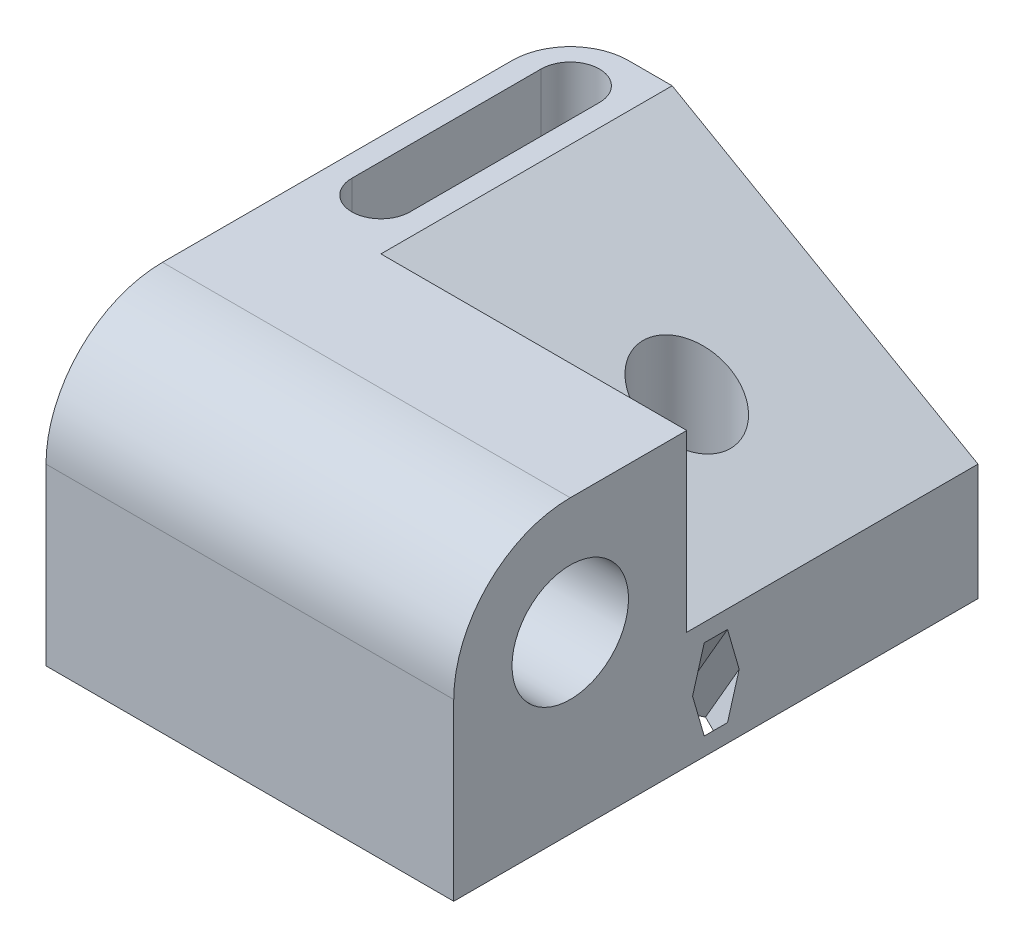
SolidWorks part; units mm, degrees
material "Cast Alloy Steel"
ref_plane "Front Plane" through (0, 0, 0) normal (0, 0, 1) x (1, 0, 0)
ref_plane "Top Plane" through (0, 0, 0) normal (0, 1, 0) x (1, 0, 0)
ref_plane "Right Plane" through (0, 0, 0) normal (1, 0, 0) x (0, 0, -1)
sketch "Sketch1" plane through (0, 0, 0) normal (0, 1, 0) x (1, 0, 0)
  line L0 (-52.5, -7.5) -> (-52.5, -72.5) construction
  line L1 (-50, -90) -> (70, -90)
  line L2 (-70, -70) -> (-70, 90)
  line L3 (-70, 90) -> (70, 90)
  line L4 (70, -90) -> (70, 90)
  line L5 (-70, -90) -> (70, 90) construction
  line L6 (-70, 90) -> (70, -90) construction
  line L7 (-42.5, -7.5) -> (-42.5, -72.5)
  line L8 (-62.5, -7.5) -> (-62.5, -72.5)
  arc A0 (-50, -90) -> (-70, -70) centre (-50, -70) cw
  arc A1 (-42.5, -7.5) -> (-62.5, -7.5) centre (-52.5, -7.5) ccw
  arc A2 (-62.5, -72.5) -> (-42.5, -72.5) centre (-52.5, -72.5) ccw
  circle A3 centre (25, -35) radius 15
  point P0 (0, 0)
  point P11 (-52.5, -40)
  dimension "D3" = 20
  dimension "D5" = 10
  dimension "D8" = 30
  dimension "D1" = 140
  dimension "D2" = 180
  dimension "D4" = 65
  dimension "D6" = 82.5
  dimension "D7" = 17.5
  dimension "D9" = 45
  dimension "D10" = 55
extrude "Boss-Extrude1" add sketch "Sketch1" along normal blind 100
sketch "Sketch2" plane through (0, 0, 90) normal (0, 0, 1) x (1, 0, 0)
  line L0 (-35, 100) -> (70, 40)
  line L1 (-50, 100) -> (70, 100) construction
  line L2 (70, 100) -> (70, 0) construction
  line L3 (70, 40) -> (70, 100)
  line L4 (70, 100) -> (-35, 100)
  dimension "D1" = 105
  dimension "D2" = 60
extrude "Cut-Extrude1" cut sketch "Sketch2" against normal blind 100
fillet "Fillet1" radius 40 1 edges at (0, 100, -90)
sketch "Sketch3" plane through (70, 0, 0) normal (1, 0, 0) x (0, 0, -1)
  line L0 (10, 40) -> (-90, 40) construction
  circle A0 centre (50, 60) radius 20
  point P2 (0, 0)
  point P3 (0, 0)
  point P4 (0, 0)
  point P5 (0, 0)
  dimension "D1" = 40
extrude "Cut-Extrude2" cut sketch "Sketch3" against normal blind 105
sketch "Sketch5" plane through (70, 0, 0) normal (1, 0, 0) x (0, 0, -1)
  line L0 (-90, 0) -> (90, 0) construction
  line L1 (90, 60) -> (90, 0) construction
  point P0 (0, 20)
  point P5 (0, 0)
  point P6 (0, 0)
  point P7 (0, 0)
  point P8 (0, 0)
  point P9 (0, 0)
  dimension "D1" = 20
  dimension "D2" = 90
ref_plane "Plane1" through (60.8013, 105.3109, 0) normal (0.5, 0.866, 0) x (0, 0, -1)
sketch "Sketch6" plane through (60.8013, 105.3109, 0) normal (0.5, 0.866, 0) x (0, 0, -1)
  line L1 (8, -50.6218) -> (4, -43.6936)
  line L2 (4, -43.6936) -> (-4, -43.6936)
  line L3 (-4, -43.6936) -> (-8, -50.6218)
  line L4 (-8, -50.6218) -> (-4, -57.55)
  line L5 (-4, -57.55) -> (4, -57.55)
  line L6 (4, -57.55) -> (8, -50.6218)
  circle A0 centre (0, -50.6218) radius 6.9282 construction
  point P1 (0, 0)
  point P9 (7.8751, -50.6218)
  point P10 (0, 0)
  point P11 (0, 0)
  point P12 (0, 0)
  point P14 (0, 0)
  point P15 (0, 0)
  point P16 (0, 0)
  dimension "D1" = 8
extrude "Cut-Extrude3" cut sketch "Sketch6" against normal through all
mirror "Mirror1" about plane through (-50, 100, 90) normal (0, 0, -1) of bodies 105
delete or keep bodies "Body-Delete/Keep 1" type delete bodies bodies 105
move or copy body "Body-Move/Copy2" bodies to move or copy 106 copy no translate (0, 0, -180) parameters "D1"=0, "D2"=0, "D3"=180
